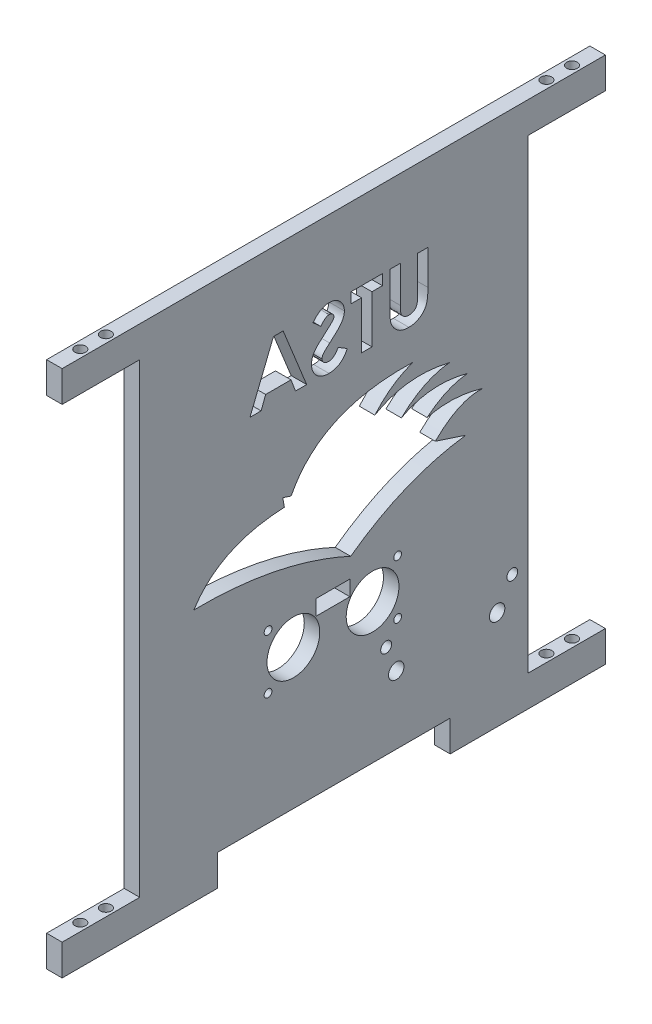
SolidWorks part; units mm, degrees
ref_plane "Front Plane" through (0, 0, 0) normal (0, 0, 1) x (1, 0, 0)
ref_plane "Top Plane" through (0, 0, 0) normal (0, 1, 0) x (1, 0, 0)
ref_plane "Right Plane" through (0, 0, 0) normal (1, 0, 0) x (0, 0, -1)
sketch "Sketch1" plane through (0, 0, 0) normal (1, 0, 0) x (0, 0, -1)
  line L0 (62.997, -55.8297) -> (88.397, -55.8297)
  line L2 (-64.003, 96.5703) -> (-64.003, -55.8297)
  line L4 (62.997, 96.5703) -> (62.997, -55.8297)
  line L6 (-89.403, -65.9897) -> (-89.403, -55.8297)
  line L7 (-89.403, -55.8297) -> (-64.003, -55.8297)
  line L8 (88.397, -65.9897) -> (88.397, -55.8297)
  line L9 (-89.403, -65.9897) -> (88.397, -65.9897)
  line L10 (-64.003, 20.3703) -> (75.8155, 20.3703) construction
  line L11 (62.997, 96.5703) -> (88.397, 96.5703)
  line L12 (88.397, 106.7303) -> (88.397, 96.5703)
  line L13 (-89.403, 106.7303) -> (88.397, 106.7303)
  line L14 (-89.403, 106.7303) -> (-89.403, 96.5703)
  line L15 (-89.403, 96.5703) -> (-64.003, 96.5703)
  dimension "D1" = 152.4
  dimension "D2" = 127
  dimension "D3" = 10.16
  dimension "D4" = 62.997
  dimension "D5" = 88.397
  dimension "D6" = 96.5703
extrude "Boss-Extrude1" add sketch "Sketch1" along normal blind 5.08
sketch "Sketch2" plane through (0, 0, 0) normal (1, 0, 0) x (0, 0, -1)
  line L6 (-89.403, -65.9897) -> (88.397, -65.9897) construction
  line L7 (37.597, -65.9897) -> (-38.603, -65.9897)
  line L8 (37.597, -65.9897) -> (37.597, -55.8297)
  line L9 (37.597, -55.8297) -> (-38.603, -55.8297)
  line L10 (-38.603, -65.9897) -> (-38.603, -55.8297)
  line L11 (62.997, -55.8297) -> (62.997, 96.5703) construction
  line L12 (-64.003, 96.5703) -> (-64.003, -55.8297) construction
  dimension "D1" = 25.4
  dimension "D2" = 25.4
extrude "Cut-Extrude3" cut sketch "Sketch2" along normal blind 22.86
sketch "Sketch5" plane through (0, 0, 0) normal (1, 0, 0) x (0, 0, -1)
  line L0 (42.6715, 21.7988) -> (32.7277, 25.0758)
  line L1 (-14.4511, 33.1423) -> (-17.1979, 34.0469)
  line L2 (-17.1979, 34.0469) -> (-16.6638, 31.0462)
  spline S0 degree 2 poles (5.0431, 6.3181) (22.6773, 19.1667) (42.6715, 21.7988) knots 0 0 0 0.792654 0.792654 0.792654
  spline S1 degree 2 poles (32.7277, 25.0758) (40.5945, 32.834) (48.3101, 32.2715) knots 0 0 0 0.556458 0.556458 0.556458
  spline S2 degree 2 poles (48.3101, 32.2715) (38.8463, 35.2531) (30.0437, 33.1423) knots 0 0 0 0.798457 0.798457 0.798457
  spline S3 degree 2 poles (30.0437, 33.1423) (36.6362, 38.5286) (43.4033, 39.0113) knots 0 0 0 0.455199 0.455199 0.455199
  spline S4 degree 2 poles (43.4033, 39.0113) (31.0595, 42.3772) (21.6264, 37.2351) knots 0 0 0 0.83745 0.83745 0.83745
  spline S5 degree 2 poles (21.6264, 37.2351) (28.9183, 44.2411) (37.3799, 45.0347) knots 0 0 0 0.665456 0.665456 0.665456
  spline S6 degree 2 poles (37.3799, 45.0347) (23.39, 48.4659) (12.9406, 42.3636) knots 0 0 0 0.846898 0.846898 0.846898
  spline S7 degree 2 poles (12.9406, 42.3636) (18.4877, 48.8496) (25.642, 51.1381) knots 0 0 0 0.61521 0.61521 0.61521
  spline S8 degree 2 poles (25.642, 51.1381) (-4.7738, 52.1544) (-14.4511, 33.1423) knots 0 0 0 0.882311 0.882311 0.882311
  spline S9 degree 2 poles (-16.6638, 31.0462) (-37.8172, 30.1818) (-46.2714, 16.7623) knots 0 0 0 0.810821 0.810821 0.810821
  spline S10 degree 2 poles (-46.2714, 16.7623) (-18.3535, 17.1257) (5.0431, 6.3181) knots 0 0 0 0.629594 0.629594 0.629594
  dimension "D1" = 5.0431
  dimension "D2" = 12.9406
  dimension "D3" = 21.6264
  dimension "D4" = 25.642
  dimension "D5" = 30.0437
  dimension "D6" = 32.7277
  dimension "D7" = 37.3799
  dimension "D8" = 42.6715
  dimension "D9" = 43.4033
  dimension "D10" = 48.3101
  dimension "D11" = 14.4511
  dimension "D12" = 16.6638
  dimension "D13" = 17.1979
  dimension "D14" = 46.2714
  dimension "D15" = 6.3181
  dimension "D16" = 16.7623
  dimension "D17" = 21.7988
  dimension "D18" = 25.0758
  dimension "D19" = 31.0462
  dimension "D20" = 32.2715
  dimension "D21" = 33.1423
  dimension "D22" = 34.0469
  dimension "D23" = 37.2351
  dimension "D24" = 39.0113
  dimension "D25" = 42.3636
  dimension "D26" = 45.0347
  dimension "D27" = 51.1381
extrude "Cut-Extrude5" cut sketch "Sketch5" along normal blind 22.86
sketch "Sketch6" plane through (0, 0, 0) normal (1, 0, 0) x (0, 0, -1)
  line L0 (-64.003, 96.5703) -> (-64.003, -55.8297) construction
  text T0 "UTSA" font "Century Gothic" height in points 72
  dimension "D1" = 96.52
  dimension "D2" = 62.1931
extrude "Cut-Extrude7" cut sketch "Sketch6" along normal blind 38.862
sketch "Sketch7" plane through (0, 0, 0) normal (0, 1, 0) x (1, 0, 0)
  line L0 (5.08, -0.4541) -> (-26.1348, -0.4541) construction
  line L1 (5.08, 88.397) -> (0, 88.397) construction
  line L2 (0, 88.397) -> (0, -89.403) construction
  circle A0 centre (2.54, 80.015) radius 1.7526
  circle A1 centre (2.54, 71.633) radius 1.7526
  circle A2 centre (2.54, -72.5413) radius 1.7526
  circle A3 centre (2.54, -80.9233) radius 1.7526
  dimension "D1" = 3.5052
  dimension "D2" = 8.382
  dimension "D3" = 8.382
  dimension "D4" = 2.54
extrude "Cut-Extrude8" cut sketch "Sketch7" against normal blind 119.38 and the other way blind 152.4
sketch "Sketch8" plane through (0, 0, 0) normal (1, 0, 0) x (0, 0, -1)
  line L0 (62.997, -55.8297) -> (62.997, 96.5703) construction
  circle A0 centre (12.197, -10.1006) radius 8.636
  circle A1 centre (-13.711, -10.1006) radius 8.636
  dimension "D1" = 17.272
  dimension "D2" = 50.8
  dimension "D3" = 25.908
  dimension "D4" = 10.1006
extrude "Cut-Extrude9" cut sketch "Sketch8" along normal blind 119.38
sketch "Sketch9" plane through (0, 0, 0) normal (1, 0, 0) x (0, 0, -1)
  line L0 (-23.458, -10.1006) -> (24.1858, -10.1006) construction
  line L1 (-23.458, 0.1544) -> (-23.458, -20.3556) construction
  line L2 (-0.803, 0.1544) -> (-0.803, -23.8564) construction
  line L3 (21.852, 0.1544) -> (-23.458, 0.1544) construction
  circle A0 centre (-22.0102, -1.2239) radius 1.27
  circle A1 centre (-22.0102, -18.9772) radius 1.27
  circle A2 centre (20.4042, -18.9772) radius 1.27
  circle A3 centre (20.4042, -1.2239) radius 1.27
  dimension "D2" = 2.54
  dimension "D1" = 1.4478
  dimension "D3" = 1.2239
sketch "Sketch10" plane through (0, 0, 0) normal (1, 0, 0) x (0, 0, -1)
extrude "Cut-Extrude10" cut sketch "Sketch9" along normal blind 119.38
sketch "Sketch13" plane through (0, 0, 0) normal (1, 0, 0) x (0, 0, -1)
  line L0 (21.852, 0.1544) -> (-23.458, 0.1544) construction
  line L1 (-6.2582, 0) -> (4.7654, 0)
  line L2 (-6.2582, 0) -> (-6.2582, -5.0038)
  line L3 (-6.2582, -5.0038) -> (4.7654, -5.0038)
  line L4 (4.7654, 0) -> (4.7654, -5.0038)
  dimension "D1" = 5.0038
  dimension "D2" = 0.1544
  dimension "D3" = 11.0236
  dimension "D4" = 6.2582
extrude "Cut-Extrude11" cut sketch "Sketch13" along normal blind 14.478
sketch "Sketch14" plane through (0, 0, 0) normal (1, 0, 0) x (0, 0, -1)
  circle A0 centre (19.9415, -33.601) radius 2.5238
  circle A1 centre (52.9615, -33.601) radius 2.5238
  dimension "D1" = 5.0477
  dimension "D2" = 33.02
  dimension "D3" = 19.9415
  dimension "D4" = 33.601
extrude "Cut-Extrude12" cut sketch "Sketch14" along normal blind 15.494
sketch "Sketch18" plane through (0, 0, 0) normal (1, 0, 0) x (0, 0, -1)
  line L0 (-19.1902, 77.8085) -> (-23.6169, 68.876)
  line L1 (-14.5263, 68.876) -> (-19.1902, 77.8085)
  line L2 (-14.5263, 68.876) -> (-23.6169, 68.876)
  dimension "D1" = 14.5263
  dimension "D2" = 19.1902
  dimension "D3" = 23.6169
  dimension "D4" = 68.876
  dimension "D5" = 77.8085
extrude "Cut-Extrude13" cut sketch "Sketch18" along normal blind 23.368
sketch "Sketch19" plane through (0, 0, 0) normal (1, 0, 0) x (0, 0, -1)
  circle A0 centre (16.642, -25.2619) radius 1.778
  circle A1 centre (57.917, -25.2619) radius 1.778
  dimension "D1" = 3.556
extrude "Cut-Extrude15" cut sketch "Sketch19" along normal blind 31.496
